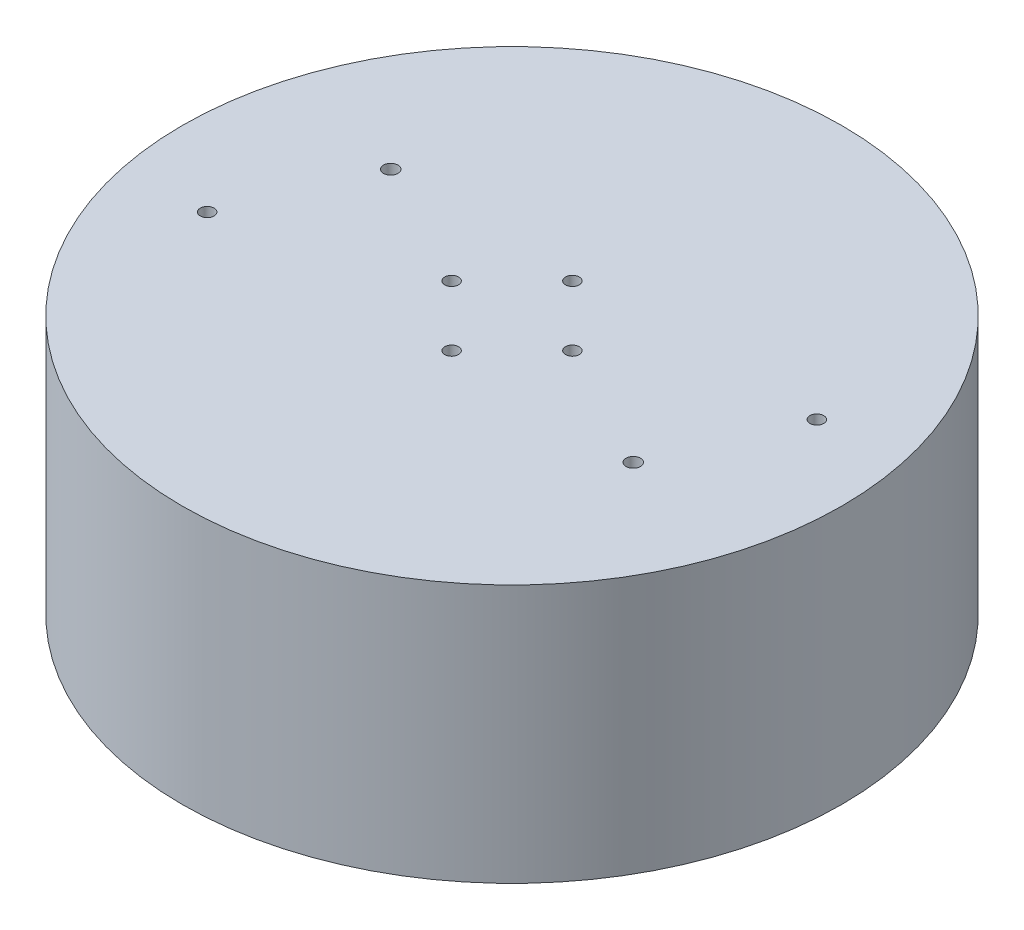
SolidWorks part; units mm, degrees
ref_plane "Front Plane" through (0, 0, 0) normal (0, 0, 1) x (1, 0, 0)
ref_plane "Top Plane" through (0, 0, 0) normal (0, 1, 0) x (1, 0, 0)
ref_plane "Right Plane" through (0, 0, 0) normal (1, 0, 0) x (0, 0, -1)
sketch "Sketch1" plane through (0, 0, 0) normal (0, 1, 0) x (1, 0, 0)
  line L0 (-58.3918, 0) -> (58.3918, 0) construction
  line L1 (0, 0) -> (-41.2892, -41.2892) construction
  line L2 (0, 62.5) -> (0, -62.5) construction
  line L3 (-68.25, 0) -> (-58.3918, 0) construction
  line L4 (0, 72.3582) -> (0, 62.5) construction
  line L5 (55, 0) -> (64.8582, 0) construction
  line L6 (6.2012, 67.9677) -> (5.3055, 58.1503) construction
  circle A0 centre (0, 0) radius 58.3918
  circle A1 centre (0, 0) radius 68.25
  ellipse E0 centre (0, 0) end of major axis (0, 62.5) minor radius 47.5 construction
  ellipse E1 centre (0, 0) end of major axis (0, 62.5) minor radius 55 construction
  ellipse E2 centre (0, 0) end of major axis (0, 72.3582) minor radius 64.8582 construction
  dimension "D5" = 136.5
  dimension "D1" = 95
  dimension "D2" = 125
  dimension "D3" = 110
  dimension "D4" = 45
extrude "Boss-Extrude1" add sketch "Sketch1" along normal blind 5
sketch "Sketch2" plane through (0, 5, 0) normal (0, 1, 0) x (1, 0, 0)
  circle A0 centre (0, 0) radius 66.25
  circle A1 centre (0, 0) radius 68.25
  circle A3 centre (0, 0) radius 68.25 construction
  dimension "D1" = 2
extrude "Boss-Extrude2" add sketch "Sketch2" along normal blind 46
sketch "Sketch5" plane through (0, 5, 0) normal (0, 1, 0) x (1, 0, 0)
  line L0 (0, 0) -> (68.25, 0) construction
  line L1 (0, 0) -> (68.0396, 5.3548) construction
  line L2 (64.9499, 2.5512) -> (64.7496, 5.0959) construction
  line L3 (64, 3.1973) -> (64, -3.1973) construction
  arc A1 (68.1496, 3.6999) -> (68.1496, -3.6999) centre (0, 0) cw construction
  circle A5 centre (0, 0) radius 65 construction
  circle A6 centre (0, 0) radius 60.9375 construction
  circle A8 centre (0, 0) radius 64.0125 construction
  circle A9 centre (0, 0) radius 68.25 construction
  arc A10 (60.9129, 1.7331) -> (60.9129, -1.7331) centre (0, 0) cw construction
  arc A11 (60.9129, 1.7331) -> (68.1496, 3.6999) centre (57.7834, 27.5441) ccw construction
  arc A12 (60.9129, -1.7331) -> (68.1496, -3.6999) centre (57.7834, -27.5441) cw construction
  arc A13 (67.0871, 1.7331) -> (67.0871, -1.7331) centre (128, 0) ccw
  arc A14 (67.0871, 1.7331) -> (59.8504, 3.6999) centre (70.2166, 27.5441) cw
  arc A15 (59.8504, 3.6999) -> (59.8504, -3.6999) centre (128, 0) ccw
  arc A16 (67.0871, -1.7331) -> (59.8504, -3.6999) centre (70.2166, -27.5441) ccw
  point P20 (64, 0)
  circle M28 centre (0, 0) radius 66.25
  dimension "Pitch Diameter" = 130
  dimension "D1" = 128.025
  dimension "D2" = 121.875
  dimension "D4" = 26
  dimension "D3" = 4.5
  dimension "D5" = 2.5525
  dimension "D6" = 64
extrude "Cut-Extrude2" cut sketch "Sketch5" against normal through all contours A16 A12 A10 A11 A14 A15 | A16 A14 A11 A10 A12 M28 | A16 A13 A14 M28
pattern_circular "CirPattern1" count 40 over 360 about axis through (0, 0, 0) along (0, 1, 0) of "Cut-Extrude2"
sketch "Sketch6" plane through (0, 5, 0) normal (0, 1, 0) x (1, 0, 0)
  circle A0 centre (0, 0) radius 60.2546
extrude "Cut-Extrude4" cut sketch "Sketch6" against normal through all
sketch "Sketch3" plane through (0, 51, 0) normal (0, 1, 0) x (1, 0, 0)
  circle A0 centre (0, 0) radius 68.25
  circle A2 centre (0, 0) radius 68.25 construction
  dimension "D1" = 136.5
extrude "Boss-Extrude3" add sketch "Sketch3" along normal blind 2.5
sketch "Sketch4" plane through (0, 53.5, 0) normal (0, 1, 0) x (1, 0, 0)
  line L0 (0, 12.5) -> (0, -12.5) construction
  line L3 (12.5, 0) -> (-12.5, 0) construction
  circle A1 centre (0, 12.5) radius 1.425
  circle A2 centre (-12.5, 0) radius 1.425
  circle A3 centre (0, -12.5) radius 1.425
  circle A4 centre (12.5, 0) radius 1.425
  circle A5 centre (0, 0) radius 12.5 construction
  dimension "D1" = 2.85
  dimension "D2" = 25
extrude "Cut-Extrude1" cut sketch "Sketch4" against normal through all
sketch "Sketch7" plane through (0, 53.5, 0) normal (0, 1, 0) x (1, 0, 0)
  circle A1 centre (-50.1478, -12.9516) radius 1.425
  circle A2 centre (-50.1478, -12.9516) radius 1.425
  circle A3 centre (-38.8281, 13.7166) radius 1.5
  circle A4 centre (-38.8281, 13.7166) radius 1.5
  dimension "D1" = 0
  dimension "D2" = 0
extrude "Cut-Extrude5" cut sketch "Sketch7" against normal blind 3.18
sketch "Sketch8" plane through (0, 53.5, 0) normal (0, 1, 0) x (1, 0, 0)
  circle A1 centre (50.1478, 12.9516) radius 1.425
  circle A2 centre (50.1478, 12.9516) radius 1.425
  circle A3 centre (38.8281, -13.7166) radius 1.5
  circle A4 centre (38.8281, -13.7166) radius 1.5
  dimension "D1" = 0
  dimension "D2" = 0
extrude "Cut-Extrude6" cut sketch "Sketch8" against normal blind 3.18
equation "\"D1@Sketch5\"=130*cos(10)"
